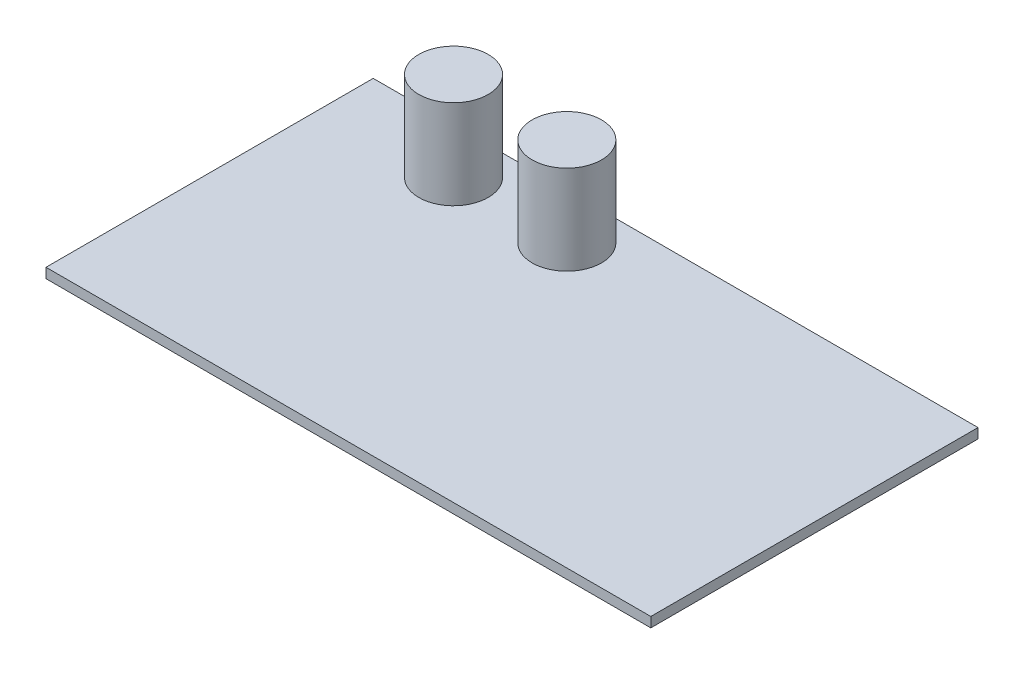
SolidWorks part; units mm, degrees
ref_plane "Front Plane" through (0, 0, 0) normal (0, 0, 1) x (1, 0, 0)
ref_plane "Top Plane" through (0, 0, 0) normal (0, 1, 0) x (1, 0, 0)
ref_plane "Right Plane" through (0, 0, 0) normal (1, 0, 0) x (0, 0, -1)
sketch "Sketch1" plane through (0, 0, 0) normal (0, 1, 0) x (1, 0, 0)
  line L1 (30.5, -16.5) -> (-30.5, -16.5)
  line L2 (30.5, -16.5) -> (30.5, 16.5)
  line L3 (30.5, 16.5) -> (-30.5, 16.5)
  line L4 (-30.5, -16.5) -> (-30.5, 16.5)
  line L5 (30.5, -16.5) -> (-30.5, 16.5) construction
  line L6 (30.5, 16.5) -> (-30.5, -16.5) construction
  point P0 (0, 0)
  dimension "D1" = 61
  dimension "D2" = 33
extrude "Boss-Extrude1" add sketch "Sketch1" along normal blind 1
sketch "Sketch2" plane through (0, 1, 0) normal (0, 1, 0) x (1, 0, 0)
  circle A0 centre (-17.7932, 11.893) radius 3.5
  circle A1 centre (-6.3635, 11.893) radius 3.5
  dimension "D1" = 7
extrude "Boss-Extrude2" add sketch "Sketch2" along normal blind 9
